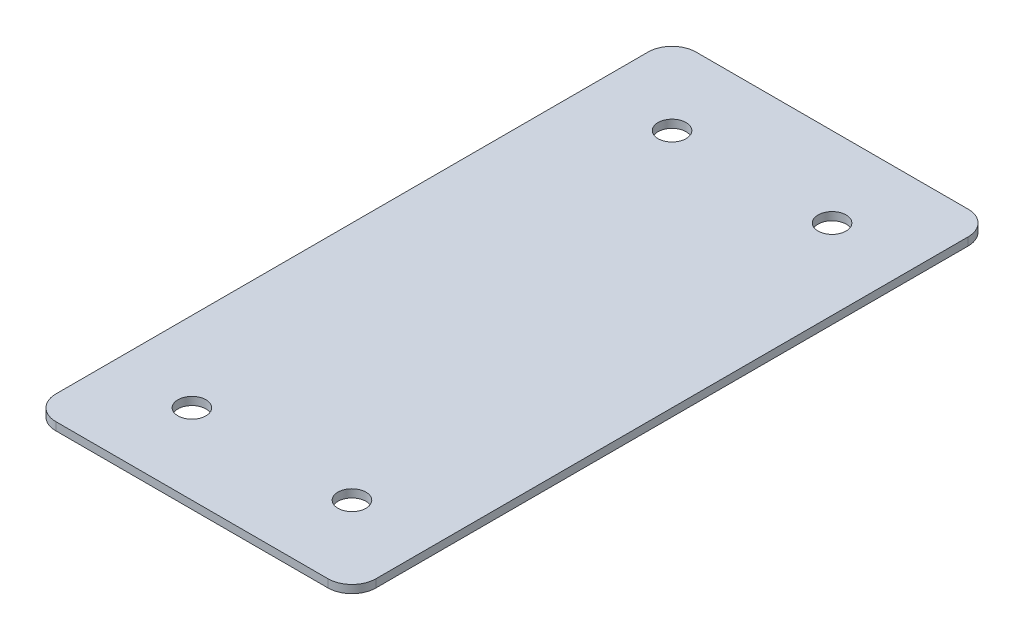
SolidWorks part; units mm, degrees
ref_plane "正面" through (0, 0, 0) normal (0, 0, 1) x (1, 0, 0)
ref_plane "平面" through (0, 0, 0) normal (0, 1, 0) x (1, 0, 0)
ref_plane "右側面" through (0, 0, 0) normal (1, 0, 0) x (0, 0, -1)
sketch "ｽｹｯﾁ1" plane through (0, 0, 0) normal (0, 1, 0) x (1, 0, 0)
  line L0 (0.2814, 39.0793) -> (0.2814, -40.9207) construction
  line L1 (-19.7186, -0.9207) -> (20.2814, -0.9207) construction
  line L2 (0.2814, 39.0793) -> (-19.7186, 39.0793)
  line L3 (-19.7186, 39.0793) -> (-19.7186, -40.9207)
  line L4 (-19.7186, -40.9207) -> (20.2814, -40.9207)
  line L5 (20.2814, -40.9207) -> (20.2814, 39.0793)
  line L6 (20.2814, 39.0793) -> (0.2814, 39.0793)
  circle A0 centre (-9.7186, 29.0793) radius 1.75
  circle A1 centre (10.2814, 29.0793) radius 1.75
  circle A2 centre (10.2814, -30.9207) radius 1.75
  circle A3 centre (-9.7186, -30.9207) radius 1.75
extrude "ﾎﾞｽ - 押し出し1" add sketch "ｽｹｯﾁ1" along normal blind 1
fillet "ﾌｨﾚｯﾄ1" radius 3 4 edges at (-19.7186, 0.5, -39.0793) (20.2814, 0.5, -39.0793) (20.2814, 0.5, 40.9207) (-19.7186, 0.5, 40.9207)
